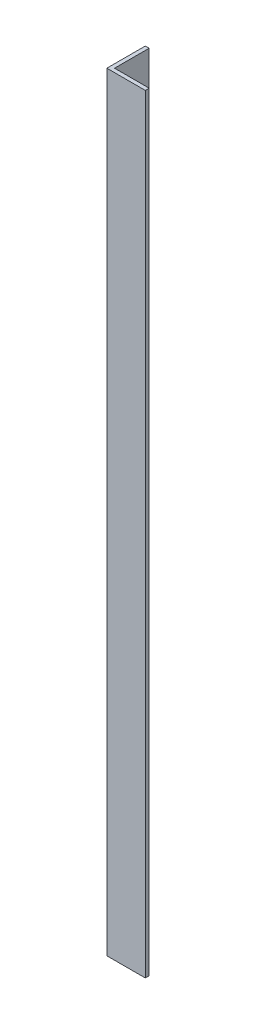
SolidWorks part; units mm, degrees
ref_plane "Front Plane" through (0, 0, 0) normal (0, 0, 1) x (1, 0, 0)
ref_plane "Top Plane" through (0, 0, 0) normal (0, 1, 0) x (1, 0, 0)
ref_plane "Right Plane" through (0, 0, 0) normal (1, 0, 0) x (0, 0, -1)
sketch "Sketch1" plane through (0, 0, 0) normal (0, 1, 0) x (1, 0, 0)
  line L0 (0, 0) -> (0, -20)
  line L1 (0, -20) -> (20, -20)
  line L2 (20, -20) -> (20, -18)
  line L3 (20, -18) -> (2, -18)
  line L4 (2, -18) -> (2, 0)
  line L5 (2, 0) -> (0, 0)
  dimension "D1" = 20
  dimension "D2" = 2
  dimension "D3" = 2
  dimension "D4" = 20
extrude "Boss-Extrude1" add sketch "Sketch1" along normal blind 400
